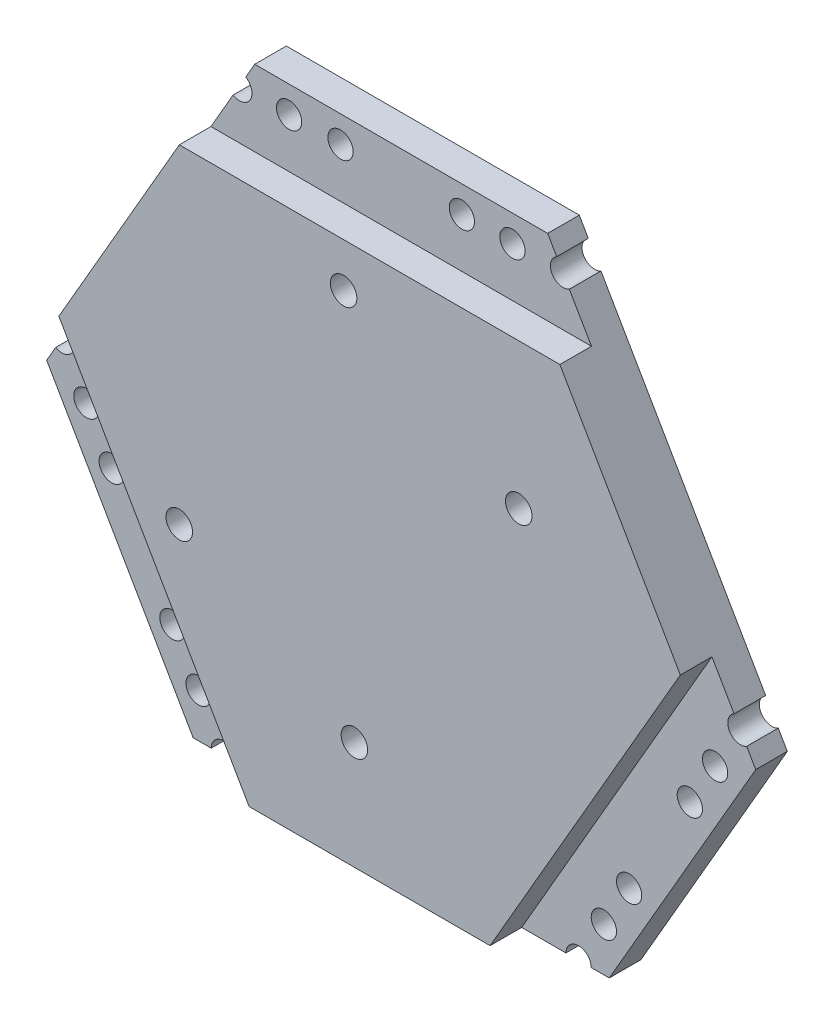
SolidWorks part; units mm, degrees
material "ABS"
ref_plane "前基準面" through (0, 0, 0) normal (0, 0, 1) x (1, 0, 0)
ref_plane "上基準面" through (0, 0, 0) normal (0, 1, 0) x (1, 0, 0)
ref_plane "右基準面" through (0, 0, 0) normal (1, 0, 0) x (0, 0, -1)
sketch "草圖1" plane through (0, 0, 0) normal (0, 0, 1) x (1, 0, 0)
  line L0 (29.3027, 33.7186) -> (37.3027, 33.7186) construction
  line L1 (45.3027, 33.7186) -> (-5.8973, 33.7186)
  line L2 (-5.8973, 33.7186) -> (-33.9573, -14.8827)
  line L3 (-33.9573, -14.8827) -> (-5.8973, 33.7186)
  line L7 (-33.9573, -14.8827) -> (-8.3573, -59.2232)
  line L8 (-8.3573, -59.2232) -> (-33.9573, -14.8827)
  line L9 (-8.3573, -59.2232) -> (47.7627, -59.2232)
  line L10 (47.7627, -59.2232) -> (73.3627, -14.8827)
  line L11 (73.3627, -14.8827) -> (45.3027, 33.7186)
  line L12 (73.3627, -14.8827) -> (69.3627, -21.8109) construction
  line L13 (-10.3973, 37.9244) -> (49.8027, 37.9244)
  line L14 (-10.3973, 37.9244) -> (-10.3973, 25.9244)
  line L15 (-10.3973, 25.9244) -> (49.8027, 25.9244)
  line L16 (49.8027, 37.9244) -> (49.8027, 25.9244)
  line L17 (-29.4573, -7.0885) -> (0.6427, -59.2232)
  line L18 (0.6427, -59.2232) -> (-9.7496, -65.2232)
  line L19 (-9.7496, -65.2232) -> (-39.8496, -13.0885)
  line L20 (-39.8496, -13.0885) -> (-29.4573, -7.0885)
  line L21 (55.7627, -45.3668) -> (51.7627, -52.295) construction
  line L22 (68.8627, -7.0885) -> (38.7627, -59.2232)
  line L23 (38.7627, -59.2232) -> (49.155, -65.2232)
  line L24 (49.155, -65.2232) -> (79.255, -13.0885)
  line L25 (79.255, -13.0885) -> (68.8627, -7.0885)
  circle A0 centre (-5.8973, 33.7186) radius 2
  circle A1 centre (1.9623, 33.7186) radius 2
  circle A2 centre (10.1027, 33.7186) radius 2
  circle A4 centre (29.3027, 33.7186) radius 2
  circle A8 centre (-33.9573, -14.8827) radius 2
  circle A9 centre (-30.0977, -21.8109) radius 2
  circle A10 centre (-26.0977, -28.7391) radius 2
  circle A12 centre (-16.4977, -45.3668) radius 2
  circle A13 centre (-12.3573, -52.295) radius 2
  circle A14 centre (-8.3573, -59.2232) radius 2
  circle A15 centre (47.7627, -59.2232) radius 2
  circle A18 centre (55.7627, -45.3668) radius 2
  circle A22 centre (37.3027, 33.7186) radius 2
  circle A23 centre (45.3027, 33.7186) radius 2
  circle A24 centre (73.3627, -14.8827) radius 2
  circle A25 centre (69.3627, -21.8109) radius 2
  circle A26 centre (65.3627, -28.7391) radius 2
  circle A27 centre (51.7627, -52.295) radius 2
  dimension "D1" = 4
  dimension "D6" = 4
  dimension "D10" = 4
  dimension "D13" = 19.2
  dimension "D11" = 4
  dimension "D15" = 19.2
  dimension "D7" = 19.2
  dimension "D17" = 8
  dimension "D2" = 8
  dimension "D3" = 120
  dimension "D4" = 120
  dimension "D5" = 56.12
  dimension "D8" = 120
  dimension "D9" = 56.12
  dimension "D12" = 8
  dimension "D16" = 56.12
  dimension "D18" = 4.5
  dimension "D19" = 4.5
  dimension "D20" = 60.2
  dimension "D21" = 12
  dimension "D22" = 90
  dimension "D23" = 180
  dimension "D24" = 12
  dimension "D25" = 4.5
  dimension "D26" = 4.5
  dimension "D27" = 8
  dimension "D28" = 12
  dimension "D29" = 60.2
  dimension "D30" = 90
  dimension "D31" = 4.5
  dimension "D14" = 3
extrude "填料-伸長4" add sketch "草圖1" along normal blind 10 contours L22 L11 L15 L3 L17 L9 | A23 L1 A22 A4 A2 A1 A0 L3 L15 L11 | A23 L11 L16 L13 L14 L3 A0 L1 A1 A2 A4 A22 | A14 L8 A13 A12 A10 A9 A8 L2 L20 L19 L18 L9 | A14 L9 L17 L2 A8 L8 A9 A10 A12 A13 | A27 L10 A15 L9 L23 L24 L25 L11 A24 A25 A26 A18 | A27 L10 A18 A26 A25 A24 L11 L22 L9 A15
sketch "草圖2" plane through (0, 0, 0) normal (0, 0, -1) x (-1, 0, 0)
  line L0 (10.3973, 25.9244) -> (29.4573, -7.0885) construction
  circle A0 centre (10.4107, -26.0987) radius 2.1
  circle A1 centre (-15.5893, 18.9346) radius 2.1
  circle A2 centre (-43.3021, 2.9346) radius 2.1
  circle A3 centre (-17.3021, -42.0987) radius 2.1
  point P4 (19.9273, 9.4179)
  dimension "D1" = 26
  dimension "D2" = 26
  dimension "D3" = 52
  dimension "D4" = 36.7696
  dimension "D6" = 4.2
  dimension "D7" = 4.2
  dimension "D5" = 2
extrude "除料-伸長1" cut sketch "草圖2" against normal through all
sketch "草圖4" plane through (0, 0, 10) normal (0, 0, 1) x (1, 0, 0)
  line L0 (38.7627, -59.2232) -> (49.155, -65.2232)
  line L1 (-10.3973, 37.9244) -> (49.8027, 37.9244)
  line L2 (-10.3973, 37.9244) -> (-10.3973, 25.9244)
  line L3 (-10.3973, 25.9244) -> (49.8027, 25.9244)
  line L4 (49.8027, 37.9244) -> (49.8027, 25.9244)
  line L5 (38.7627, -59.2232) -> (68.8722, -7.072)
  line L6 (49.155, -65.2232) -> (79.2645, -13.072)
  line L7 (68.8722, -7.072) -> (79.2645, -13.072)
  line L8 (-29.4573, -7.0885) -> (-39.8496, -13.0885)
  line L9 (-29.4573, -7.0885) -> (0.9201, -59.7038)
  line L10 (-39.8496, -13.0885) -> (-9.4722, -65.7038)
  line L11 (0.9201, -59.7038) -> (-9.4722, -65.7038)
extrude "除料-伸長2" cut sketch "草圖4" against normal blind 5
sketch "草圖7" plane through (-19.0236, 10.9833, 0) normal (-0.866, 0.5, 0) x (0, 0, 1)
  line L0 (0, -5.7866) -> (10, -5.7866)
  line L1 (0, -5.7866) -> (0, 46.268)
  line L2 (10, -5.7866) -> (10, 46.268)
  line L3 (0, 46.268) -> (10, 46.268)
  line L4 (0, 17.2525) -> (0, -20.8675) construction
  line L5 (10, 17.2525) -> (10, -20.8675) construction
  line L6 (0, -5.7866) -> (10, -5.7866)
  line L7 (0, -5.7866) -> (0, -53.8162)
  line L8 (10, -5.7866) -> (10, -53.8162)
  line L9 (0, -53.8162) -> (10, -53.8162)
  line M2 (0, -20.8675) -> (5, -20.8675)
  line M3 (5, -20.8675) -> (10, -20.8675)
  line M5 (10, 17.2525) -> (5, 17.2525)
  line M6 (5, 17.2525) -> (0, 17.2525)
extrude "除料-伸長9" cut sketch "草圖7" along direction (-0.866, 0.5, 0) on the side of the normal through all contours L7 L9 L8 M3 M2 | L3 L1 L2 M6 M5
sketch "草圖8" plane through (0, 0, 0) normal (0, 0, -1) x (-1, 0, 0)
  line L0 (-19.7041, -31.9385) -> (2.8126, -18.9385)
  line L1 (-19.7041, -31.9385) -> (-35.7041, -4.2256)
  line L2 (2.8126, -18.9385) -> (-13.1874, 8.7744)
  line L3 (-35.7041, -4.2256) -> (-13.1874, 8.7744)
  circle A0 centre (-17.3021, -42.0987) radius 2.1 construction
  circle A1 centre (10.4107, -26.0987) radius 2.1 construction
  circle A4 centre (10.4107, -26.0987) radius 2.1 construction
  dimension "D3" = 10
  dimension "D4" = 10
  dimension "D5" = 3
  dimension "D1" = 32
  dimension "D2" = 26
extrude "填料-伸長5" add sketch "草圖8" along normal blind 3
sketch "草圖9" plane through (0, 0, -3) normal (0, 0, -1) x (-1, 0, 0)
  line L0 (-19.338, -30.5724) -> (1.4466, -18.5724)
  line L1 (-19.338, -30.5724) -> (-34.338, -4.5917)
  line L2 (1.4466, -18.5724) -> (-13.5534, 7.4083)
  line L3 (-34.338, -4.5917) -> (-13.5534, 7.4083)
  line L4 (-13.1874, 8.7744) -> (-35.7041, -4.2256) construction
  line L6 (-35.7041, -4.2256) -> (-19.7041, -31.9385) construction
  dimension "D1" = 30
  dimension "D2" = 24
  dimension "D3" = 1
  dimension "D4" = 1
  dimension "D5" = 1
extrude "除料-伸長10" cut sketch "草圖9" against normal blind 6
fillet "圓角1" radius 2 4 edges at (13.5534, 7.4083, 0) (-1.4466, -18.5724, 0) (34.338, -4.5917, 0) (19.338, -30.5724, 0)
fillet "圓角2" radius 2 4 edges at (-2.8126, -18.9385, -1.5) (13.1874, 8.7744, -1.5) (35.7041, -4.2256, -1.5) (19.7041, -31.9385, -1.5)
sketch "草圖10" plane through (0, 0, 3) normal (0, 0, -1) x (-1, 0, 0)
  line L0 (-2.3034, -12.0772) -> (-9.8034, 0.9131)
  line L1 (-2.3034, -12.0772) -> (-23.0879, -24.0771)
  line L2 (-15.2855, 6.4083) -> (-32.606, -3.5917) construction
  line L3 (-33.338, -6.3237) -> (-20.338, -28.8404) construction
  line L4 (-9.8034, 0.9131) -> (-30.5879, -11.0868)
  line L5 (-23.0879, -24.0771) -> (-30.5879, -11.0868)
  line L6 (0.4466, -16.8404) -> (-12.5534, 5.6763) construction
  circle A0 centre (-28.1909, -6.2388) radius 0.65
  circle A1 centre (-15.2005, 1.2612) radius 0.65
  circle A2 centre (-4.7005, -16.9253) radius 0.65
  circle A3 centre (-17.6909, -24.4253) radius 0.65
  dimension "D1" = 1.3
  dimension "D4" = 4.5
  dimension "D6" = 3
  dimension "D7" = 3
  dimension "D5" = 4.5
  dimension "D2" = 2
  dimension "D3" = 2
extrude "除料-伸長11" cut sketch "草圖10" against normal blind 6
sketch "草圖12" plane through (48.5776, 28.0463, 0) normal (0.866, 0.5, 0) x (0, 0, -1)
  line L0 (0, -23.6856) -> (-10, -23.6856)
  line L1 (0, -23.6856) -> (0, -70.3801)
  line L2 (-10, -23.6856) -> (-10, -70.3801)
  line L3 (0, -70.3801) -> (-10, -70.3801)
  line L4 (0, -40.5702) -> (0, -2.4502) construction
  line L5 (-10, -40.5702) -> (-10, -2.4502) construction
  line L6 (0, -23.6856) -> (-10, -23.6856)
  line L7 (0, -23.6856) -> (0, 27.878)
  line L8 (-10, -23.6856) -> (-10, 27.878)
  line L9 (0, 27.878) -> (-10, 27.878)
  line M2 (0, -2.4502) -> (-5, -2.4502)
  line M3 (-5, -2.4502) -> (-10, -2.4502)
  line M5 (-10, -40.5702) -> (-5, -40.5702)
  line M6 (-5, -40.5702) -> (0, -40.5702)
extrude "除料-伸長12" cut sketch "草圖12" along normal through all contours L3 L1 L2 M6 M5 | L7 L9 L8 M3 M2
sketch "草圖13" plane through (0, -59.2232, 0) normal (0, -1, 0) x (1, 0, 0)
  line L0 (19.7027, 10) -> (19.7027, 0)
  line L1 (19.7027, 10) -> (-25.3386, 10)
  line L2 (19.7027, 0) -> (-25.3386, 0)
  line L3 (-25.3386, 10) -> (-25.3386, 0)
  line L4 (0.6427, 10) -> (38.7627, 10) construction
  line L5 (0.6427, 0) -> (38.7627, 0) construction
  line L6 (19.7027, 10) -> (19.7027, 0)
  line L7 (19.7027, 10) -> (66.2602, 10)
  line L8 (19.7027, 0) -> (66.2602, 0)
  line L9 (66.2602, 10) -> (66.2602, 0)
  line M2 (38.7627, 0) -> (38.7627, 5)
  line M3 (38.7627, 5) -> (38.7627, 10)
  line M5 (0.6427, 10) -> (0.6427, 5)
  line M6 (0.6427, 5) -> (0.6427, 0)
extrude "除料-伸長13" cut sketch "草圖13" along normal through all contours L9 L7 L8 M3 M2 | L1 L3 L2 M6 M5
